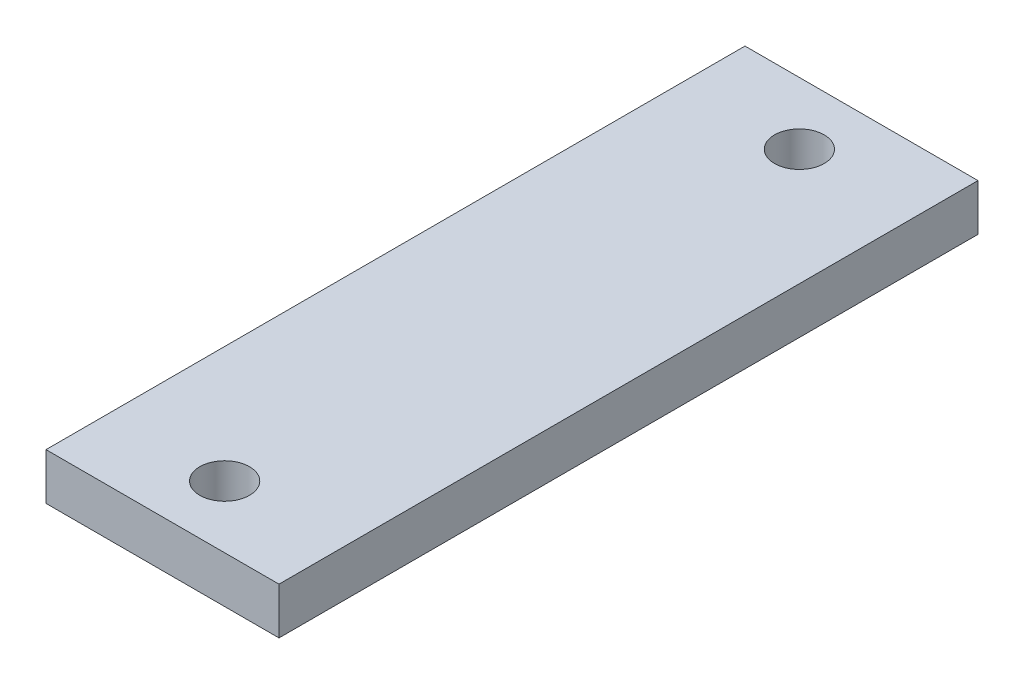
SolidWorks part; units mm, degrees
ref_plane "Front Plane" through (0, 0, 0) normal (0, 0, 1) x (1, 0, 0)
ref_plane "Top Plane" through (0, 0, 0) normal (0, 1, 0) x (1, 0, 0)
ref_plane "Right Plane" through (0, 0, 0) normal (1, 0, 0) x (0, 0, -1)
sketch "Sketch1" plane through (0, 0, 0) normal (0, 1, 0) x (1, 0, 0)
  line L1 (0, 0) -> (15, 0)
  line L2 (0, 0) -> (0, 45)
  line L3 (0, 45) -> (15, 45)
  line L4 (15, 0) -> (15, 45)
  dimension "D1" = 45
  dimension "D2" = 15
extrude "Boss-Extrude1" add sketch "Sketch1" along normal blind 3 contours L2 L3 L4 L1
sketch "Sketch2" plane through (0, 3, 0) normal (0, 1, 0) x (1, 0, 0)
  circle A0 centre (7.5, 4) radius 1.6
  circle A1 centre (7.5, 41) radius 1.6
extrude "Cut-Extrude1" cut sketch "Sketch2" against normal blind 3
